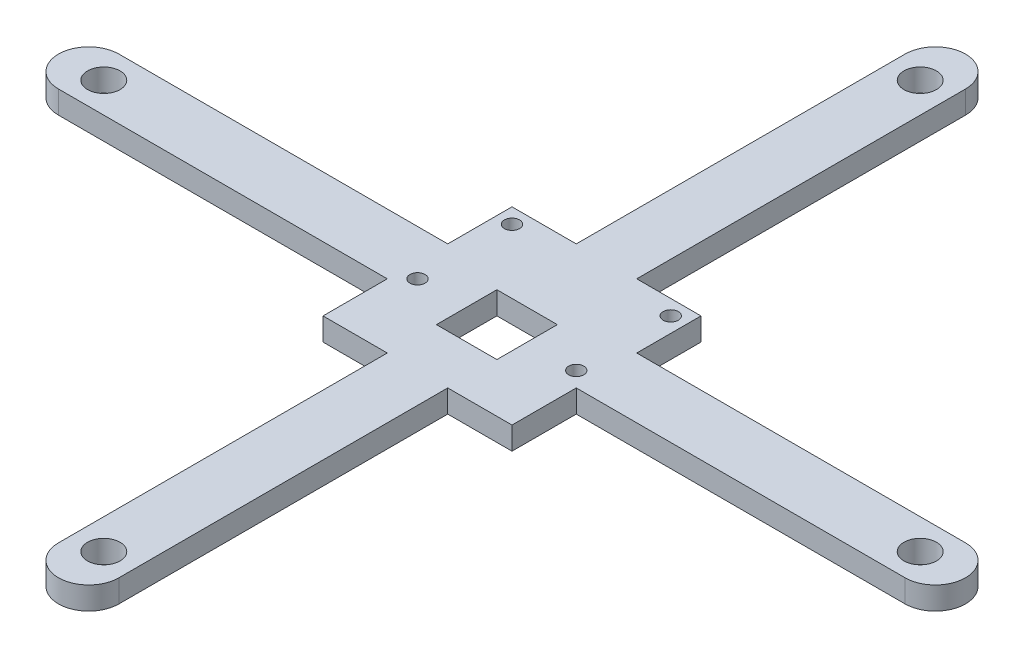
SolidWorks part; units mm, degrees
ref_plane "Piano frontale" through (0, 0, 0) normal (0, 0, 1) x (1, 0, 0)
ref_plane "Piano superiore" through (0, 0, 0) normal (0, 1, 0) x (1, 0, 0)
ref_plane "Piano destro" through (0, 0, 0) normal (1, 0, 0) x (0, 0, -1)
sketch "Schizzo1" plane through (0, 0, 0) normal (0, 1, 0) x (1, 0, 0)
  line L6 (4, 55.9988) -> (4, 12.5)
  line L8 (-60, 0) -> (60, 0) construction
  line L9 (0, 60) -> (0, -60) construction
  line L10 (-4, 12.5) -> (-4, 55.9988)
  line L11 (12.5, -4) -> (55.9988, -4)
  line L12 (4, -12.5) -> (4, -55.9988)
  line L13 (12.5, 4) -> (55.9988, 4)
  line L14 (-10.5, 10.5) -> (10.5, 10.5) construction
  line L15 (-12.5, -12.5) -> (-4, -12.5)
  line L16 (-12.5, -12.5) -> (-12.5, -4)
  line L17 (-12.5, 12.5) -> (-4, 12.5)
  line L18 (12.5, -12.5) -> (12.5, -4)
  line L19 (-12.5, -12.5) -> (12.5, 12.5) construction
  line L20 (-12.5, 12.5) -> (12.5, -12.5) construction
  line L21 (-10.5, 10.5) -> (-10.5, -2) construction
  line L22 (-10.5, -2) -> (10.5, -2) construction
  line L23 (10.5, -2) -> (10.5, 10.5) construction
  line L24 (-4, -55.9988) -> (-4, -12.5)
  line L25 (-4, -6) -> (4, -6)
  line L26 (-4, -6) -> (-4, 2)
  line L27 (-4, 2) -> (4, 2)
  line L28 (4, -6) -> (4, 2)
  line L29 (-4, -6) -> (4, 2) construction
  line L30 (-4, 2) -> (4, -6) construction
  line L31 (-55.9988, -4) -> (-12.5, -4)
  line L32 (-55.9988, 4) -> (-12.5, 4)
  line L33 (-55.9988, 4) -> (-55.9988, -4) construction
  line L34 (55.9988, 4) -> (55.9988, -4) construction
  line L35 (-4, 55.9988) -> (4, 55.9988) construction
  line L36 (-4, -55.9988) -> (4, -55.9988) construction
  line L37 (-12.5, 4) -> (-12.5, 12.5)
  line L38 (12.5, 4) -> (12.5, 12.5)
  line L39 (4, -12.5) -> (12.5, -12.5)
  line L40 (4, 12.5) -> (12.5, 12.5)
  circle A0 centre (-10.5, 10.5) radius 1
  circle A1 centre (10.5, 10.5) radius 1
  circle A2 centre (-10.5, -2) radius 1
  circle A3 centre (10.5, -2) radius 1
  circle A4 centre (-54, 0) radius 2.15
  circle A5 centre (0, 0) radius 54 construction
  circle A6 centre (0, 54) radius 2.15
  circle A7 centre (54, 0) radius 2.15
  circle A8 centre (0, -54) radius 2.15
  circle A9 centre (0, 0) radius 60 construction
  arc A10 (-55.9988, 4) -> (-55.9988, -4) centre (-56, 0) ccw
  arc A13 (-4, -55.9988) -> (4, -55.9988) centre (0, -55.9988) ccw
  arc A14 (55.9988, -4) -> (55.9988, 4) centre (56, 0) ccw
  arc A15 (4, 55.9988) -> (-4, 55.9988) centre (0, 56) ccw
  point P2 (0, 10.5)
  point P14 (0, 0)
  point P15 (0, 0)
  point P17 (0, 0)
  point P18 (0, 0)
  point P39 (0, -2)
  dimension "D5" = 2
  dimension "D8" = 4.3
  dimension "D9" = 108
  dimension "D11" = 120
  dimension "D2" = 25
  dimension "D3" = 21
  dimension "D4" = 2
  dimension "D6" = 12.5
  dimension "D7" = 8
  dimension "D10" = 112
  dimension "D12" = 8
  dimension "D13" = 43.4988
extrude "Estrusione-Estrusione1" add sketch "Schizzo1" along normal blind 3
